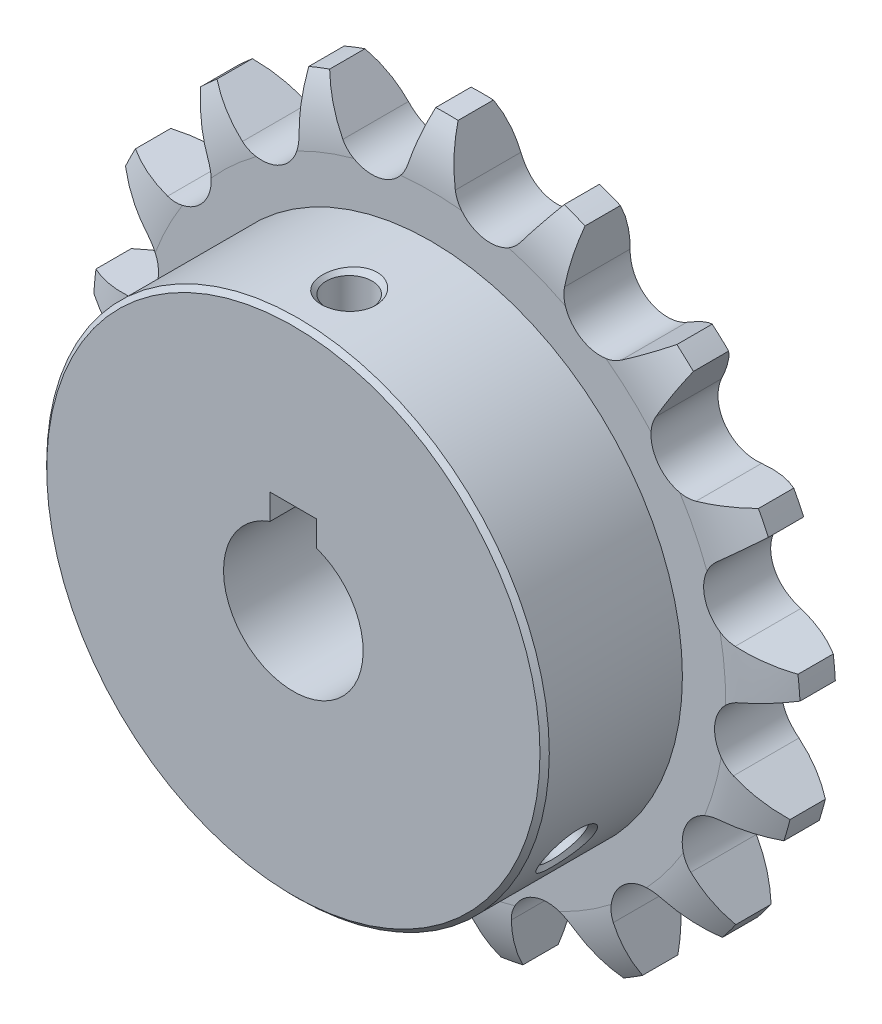
SolidWorks part; units mm, degrees
ref_plane "Front Plane" through (0, 0, 0) normal (0, 0, 1) x (1, 0, 0)
ref_plane "Top Plane" through (0, 0, 0) normal (0, 1, 0) x (1, 0, 0)
ref_plane "Right Plane" through (0, 0, 0) normal (1, 0, 0) x (0, 0, -1)
ref_plane "Plane1" through (0, 0, 0) normal (1, 0, 0) x (0, 0, -1)
sketch "Sketch1" plane through (0, 0, 0) normal (1, 0, 0) x (0, 0, -1)
  line L0 (-22, 7.5) -> (0, 7.5)
  line L1 (0, 7.5) -> (0, 31.6496)
  line L2 (-1.7016, 38) -> (-5.4984, 38)
  line L3 (-7.2, 31.6496) -> (-7.2, 27)
  line L4 (-7.2, 27) -> (-21.5, 27)
  line L5 (-21.5, 27) -> (-22, 26.5)
  line L6 (-22, 26.5) -> (-22, 7.5)
  line L7 (0, 0) -> (-3.6, 0) construction
  arc A0 (0, 31.6496) -> (-1.7016, 38) centre (-12.7008, 31.6496) ccw
  arc A1 (-5.4984, 38) -> (-7.2, 31.6496) centre (5.5008, 31.6496) ccw
revolve "Revolve1" add sketch "Sketch1" angle 360 about L7
ref_plane "Plane2" through (0, 0, 0) normal (0, 0, 1) x (1, 0, 0)
sketch "Sketch2" plane through (0, 0, 0) normal (0, 0, 1) x (1, 0, 0)
  line L0 (-37.9482, 2.3161) -> (-33.0556, 0.5314)
  line L1 (-32.3951, -6.5963) -> (-36.8765, -9.2496)
  line L2 (-36.8765, -9.2496) -> (-36.2223, -11.5488)
  line L3 (-36.2223, -11.5488) -> (-31.0154, -11.4455)
  line L4 (-27.8246, -17.8533) -> (-31.0449, -21.9463)
  line L5 (-31.0449, -21.9463) -> (-29.6044, -23.8539)
  line L6 (-29.6044, -23.8539) -> (-24.7864, -21.8766)
  line L7 (-19.4963, -26.6992) -> (-21.0206, -31.6791)
  line L8 (-21.0206, -31.6791) -> (-18.9882, -32.9374)
  line L9 (-18.9882, -32.9374) -> (-15.2098, -29.3532)
  line L10 (-8.5349, -31.9391) -> (-8.1573, -37.1334)
  line L11 (-8.1573, -37.1334) -> (-5.8076, -37.5726)
  line L12 (-5.8076, -37.5726) -> (-3.5791, -32.8655)
  line L13 (3.5791, -32.8655) -> (5.8076, -37.5726)
  line L14 (5.8076, -37.5726) -> (8.1573, -37.1334)
  line L15 (8.1573, -37.1334) -> (8.5349, -31.9391)
  line L16 (15.2098, -29.3532) -> (18.9882, -32.9374)
  line L17 (18.9882, -32.9374) -> (21.0206, -31.6791)
  line L18 (21.0206, -31.6791) -> (19.4963, -26.6992)
  line L19 (24.7864, -21.8766) -> (29.6044, -23.8539)
  line L20 (29.6044, -23.8539) -> (31.0449, -21.9463)
  line L21 (31.0449, -21.9463) -> (27.8246, -17.8533)
  line L22 (31.0154, -11.4455) -> (36.2223, -11.5488)
  line L23 (36.2223, -11.5488) -> (36.8765, -9.2496)
  line L24 (36.8765, -9.2496) -> (32.3951, -6.5963)
  line L25 (33.0556, 0.5314) -> (37.9482, 2.3161)
  line L26 (37.9482, 2.3161) -> (37.7276, 4.6963)
  line L27 (37.7276, 4.6963) -> (32.5904, 5.5516)
  line L28 (30.6314, 12.4366) -> (34.5489, 15.8682)
  line L29 (34.5489, 15.8682) -> (33.4835, 18.0079)
  line L30 (33.4835, 18.0079) -> (28.3842, 16.9497)
  line L31 (24.0703, 22.6621) -> (26.4837, 27.2771)
  line L32 (26.4837, 27.2771) -> (24.7172, 28.8875)
  line L33 (24.7172, 28.8875) -> (20.3445, 26.0586)
  line L34 (14.2584, 29.827) -> (14.8417, 35.0022)
  line L35 (14.8417, 35.0022) -> (12.6127, 35.8657)
  line L36 (12.6127, 35.8657) -> (9.5572, 31.6482)
  line L37 (2.5208, 32.9636) -> (1.1952, 38)
  line L38 (1.1952, 38) -> (-1.1952, 38)
  line L39 (-1.1952, 38) -> (-2.5208, 32.9636)
  line L40 (-9.5572, 31.6482) -> (-12.6127, 35.8657)
  line L41 (-12.6127, 35.8657) -> (-14.8417, 35.0022)
  line L42 (-14.8417, 35.0022) -> (-14.2584, 29.827)
  line L43 (-20.3445, 26.0586) -> (-24.7172, 28.8875)
  line L44 (-24.7172, 28.8875) -> (-26.4837, 27.2771)
  line L45 (-26.4837, 27.2771) -> (-24.0703, 22.6621)
  line L46 (-28.3842, 16.9497) -> (-33.4835, 18.0079)
  line L47 (-33.4835, 18.0079) -> (-34.5489, 15.8682)
  line L48 (-34.5489, 15.8682) -> (-30.6314, 12.4366)
  line L49 (-32.5904, 5.5516) -> (-37.7276, 4.6963)
  line L50 (-37.7276, 4.6963) -> (-37.9482, 2.3161)
  circle A0 centre (0, 0) radius 69.12
  arc A1 (-33.0556, 0.5314) -> (-32.3951, -6.5963) centre (-34.4126, -3.1888) cw
  arc A2 (-31.0154, -11.4455) -> (-27.8246, -17.8533) centre (-30.9368, -15.4047) cw
  arc A3 (-24.7864, -21.8766) -> (-19.4963, -26.6992) centre (-23.2829, -25.5401) cw
  arc A4 (-15.2098, -29.3532) -> (-8.5349, -31.9391) centre (-12.4845, -32.2262) cw
  arc A5 (-3.5791, -32.8655) -> (3.5791, -32.8655) centre (0, -34.56) cw
  arc A6 (8.5349, -31.9391) -> (15.2098, -29.3532) centre (12.4845, -32.2262) cw
  arc A7 (19.4963, -26.6992) -> (24.7864, -21.8766) centre (23.2829, -25.5401) cw
  arc A8 (27.8246, -17.8533) -> (31.0154, -11.4455) centre (30.9368, -15.4047) cw
  arc A9 (32.3951, -6.5963) -> (33.0556, 0.5314) centre (34.4126, -3.1888) cw
  arc A10 (32.5904, 5.5516) -> (30.6314, 12.4366) centre (33.2407, 9.4578) cw
  arc A11 (28.3842, 16.9497) -> (24.0703, 22.6621) centre (27.5795, 20.8271) cw
  arc A12 (20.3445, 26.0586) -> (14.2584, 29.827) centre (18.1935, 29.3835) cw
  arc A13 (9.5572, 31.6482) -> (2.5208, 32.9636) centre (6.3504, 33.9716) cw
  arc A14 (-2.5208, 32.9636) -> (-9.5572, 31.6482) centre (-6.3504, 33.9716) cw
  arc A15 (-14.2584, 29.827) -> (-20.3445, 26.0586) centre (-18.1935, 29.3835) cw
  arc A16 (-24.0703, 22.6621) -> (-28.3842, 16.9497) centre (-27.5795, 20.8271) cw
  arc A17 (-30.6314, 12.4366) -> (-32.5904, 5.5516) centre (-33.2407, 9.4578) cw
extrude "Cut-Extrude1" cut sketch "Sketch2" along normal blind 7.2
ref_plane "Plane3" through (0, 0, 16) normal (0, 0, 1) x (1, 0, 0)
sketch "Sketch3" plane through (0, 0, 16) normal (0, 0, 1) x (1, 0, 0)
  line L0 (0, 27) -> (3, 27)
  line L1 (3, 27) -> (2.4585, 26.4585)
  line L2 (2.4585, 26.4585) -> (2.4585, 0)
  line L3 (2.4585, 0) -> (0, 0)
  line L4 (0, 0) -> (0, 27)
  line L5 (0, 0) -> (0, 27) construction
revolve "Cut-Revolve1" cut sketch "Sketch3" angle 360 about L5
cosmetic thread "Cosmetic Thread1" parameters "D1"=17.2, "D2"=6
ref_plane "Plane4" through (0, 0, 16) normal (0, 0, 1) x (1, 0, 0)
sketch "Sketch4" plane through (0, 0, 16) normal (0, 0, 1) x (1, 0, 0)
  line L0 (23.3827, -13.5) -> (21.8827, -16.0981)
  line L1 (21.8827, -16.0981) -> (21.6845, -15.3584)
  line L2 (21.6845, -15.3584) -> (-1.2293, -2.1291)
  line L3 (-1.2293, -2.1291) -> (0, 0)
  line L4 (0, 0) -> (23.3827, -13.5)
  line L5 (0, 0) -> (23.3827, -13.5) construction
revolve "Cut-Revolve2" cut sketch "Sketch4" angle 360 about L5
cosmetic thread "Cosmetic Thread2" parameters "D1"=19.5, "D2"=6
ref_plane "Plane5" through (0, 0, 0) normal (0, 0, 1) x (1, 0, 0)
sketch "Sketch5" plane through (0, 0, 0) normal (0, 0, 1) x (1, 0, 0)
  line L0 (-2.5, 9.8) -> (-2.5, 0)
  line L1 (-2.5, 0) -> (2.5, 0)
  line L2 (2.5, 0) -> (2.5, 9.8)
  line L3 (2.5, 9.8) -> (-2.5, 9.8)
extrude "Cut-Extrude2" cut sketch "Sketch5" along normal blind 22
